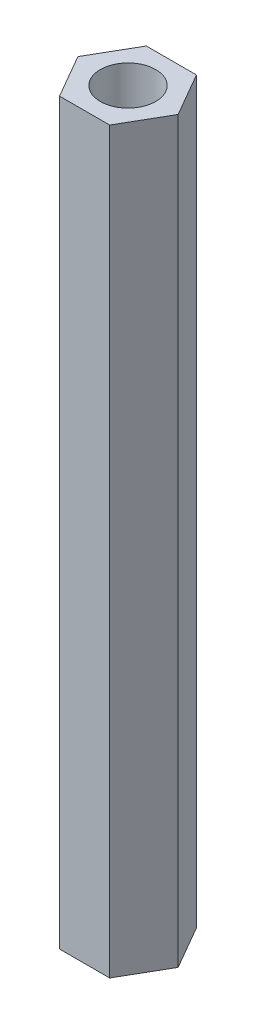
SolidWorks part; units mm, degrees
material "黄铜"
ref_plane "前视基准面" through (0, 0, 0) normal (0, 0, 1) x (1, 0, 0)
ref_plane "上视基准面" through (0, 0, 0) normal (0, 1, 0) x (1, 0, 0)
ref_plane "右视基准面" through (0, 0, 0) normal (1, 0, 0) x (0, 0, -1)
sketch "草图1" plane through (0, 0, 0) normal (0, 1, 0) x (1, 0, 0)
  line L1 (2.7135, 0) -> (1.3568, 2.35)
  line L2 (1.3568, 2.35) -> (-1.3568, 2.35)
  line L3 (-1.3568, 2.35) -> (-2.7135, 0)
  line L4 (-2.7135, 0) -> (-1.3568, -2.35)
  line L5 (-1.3568, -2.35) -> (1.3568, -2.35)
  line L6 (1.3568, -2.35) -> (2.7135, 0)
  circle A0 centre (0, 0) radius 1.5
  circle A1 centre (0, 0) radius 2.35 construction
  dimension "D1" = 3
  dimension "D2" = 4.7
extrude "凸台-拉伸1" add sketch "草图1" along normal blind 40
